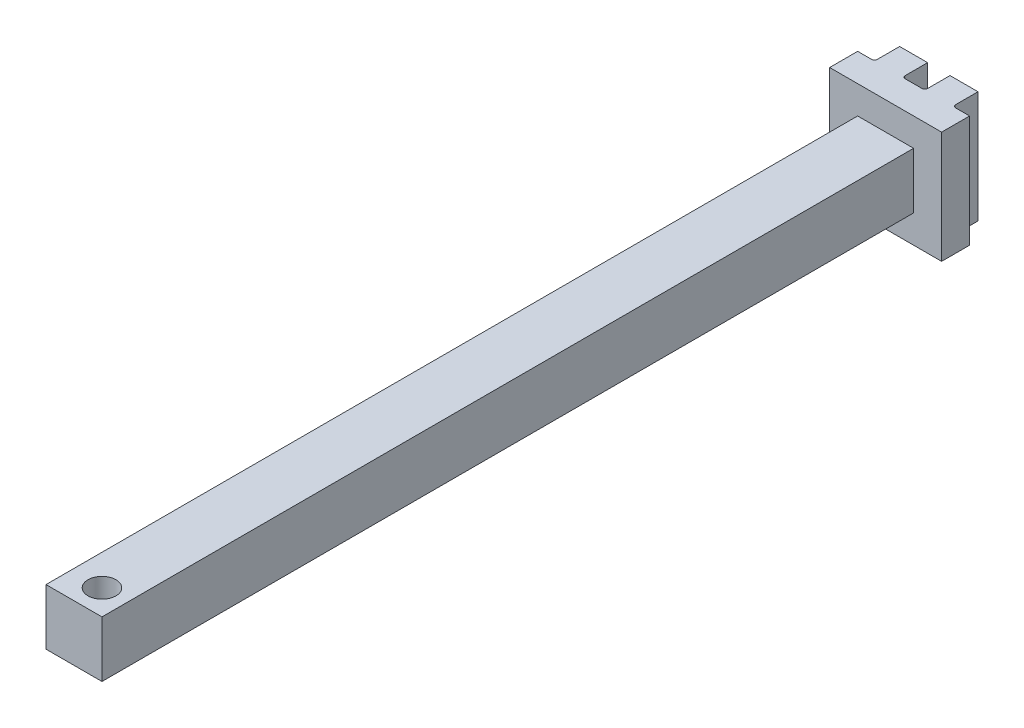
SolidWorks part; units mm, degrees
ref_plane "Front Plane" through (0, 0, 0) normal (0, 0, 1) x (1, 0, 0)
ref_plane "Top Plane" through (0, 0, 0) normal (0, 1, 0) x (1, 0, 0)
ref_plane "Right Plane" through (0, 0, 0) normal (1, 0, 0) x (0, 0, -1)
other "Configuration Table"
sketch "Sketch2" plane through (0, 0, 0) normal (0, 0, 1) x (1, 0, 0)
  line L1 (0, 0) -> (100, 0)
  line L2 (0, 0) -> (0, 100)
  line L3 (0, 100) -> (100, 100)
  line L4 (100, 0) -> (100, 100)
  dimension "D1" = 100
  dimension "D2" = 100
extrude "Boss-Extrude1" add sketch "Sketch2" along normal blind 1500
sketch "Sketch3" plane through (0, 0, 0) normal (0, -1, 0) x (1, 0, 0)
  line L0 (0, 1500) -> (100, 1500) construction
  line L1 (100, 1500) -> (100, 0) construction
  circle A0 centre (55, 1455) radius 25
  dimension "D1" = 50
  dimension "D2" = 45
  dimension "D3" = 45
extrude "Cut-Extrude1" cut sketch "Sketch3" against normal up to next
sketch "Sketch4" plane through (0, 0, 0) normal (0, 0, -1) x (-1, 0, 0)
  line L0 (0, 0) -> (-100, 0) construction
  line L1 (50, -50) -> (-150, -50)
  line L2 (50, -50) -> (50, 150)
  line L3 (50, 150) -> (-150, 150)
  line L4 (-150, -50) -> (-150, 150)
  line L5 (-100, 0) -> (-100, 100) construction
  line L6 (-100, 100) -> (0, 100) construction
  line L7 (0, 100) -> (0, 0) construction
  dimension "D1" = 50
  dimension "D2" = 50
  dimension "D3" = 50
  dimension "D4" = 50
extrude "Boss-Extrude2" add sketch "Sketch4" against normal blind 50
sketch "Sketch5" plane through (0, -50, 0) normal (0, -1, 0) x (1, 0, 0)
  line L0 (150, 0) -> (-50, 0) construction
  line L1 (-20, 0) -> (30, 0)
  line L2 (-20, 0) -> (-20, -45)
  line L3 (-20, -45) -> (30, -45)
  line L4 (30, 0) -> (30, -45)
  line L5 (50, 37.3413) -> (50, -66.8006) construction
  line L6 (70, 0) -> (120, 0)
  line L7 (70, 0) -> (70, -45)
  line L8 (70, -45) -> (120, -45)
  line L9 (120, 0) -> (120, -45)
  line L10 (100, 50) -> (0, 50) construction
  point P12 (50, 50)
  dimension "D1" = 45
  dimension "D2" = 50
  dimension "D3" = 20
extrude "Boss-Extrude3" add sketch "Sketch5" against normal up to surface (200 mm away) up to face at (50, 150, 25)
fillet "Fillet1" radius 5 10 edges at (120, 50, 0) (70, 50, 0)
